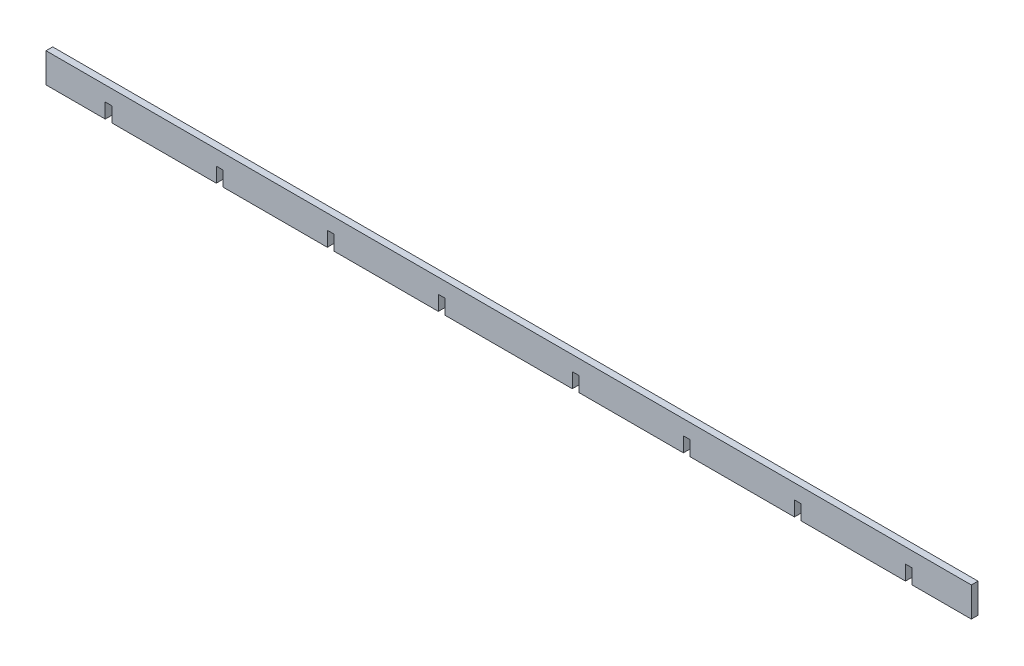
SolidWorks part; units mm, degrees
ref_plane "Front Plane" through (0, 0, 0) normal (0, 0, 1) x (1, 0, 0)
ref_plane "Top Plane" through (0, 0, 0) normal (0, 1, 0) x (1, 0, 0)
ref_plane "Right Plane" through (0, 0, 0) normal (1, 0, 0) x (0, 0, -1)
sketch "Sketch1" plane through (0, 0, 0) normal (0, 0, 1) x (1, 0, 0)
  line L0 (300, -40) -> (300, 40) construction
  line L1 (-178, 40) -> (2322, 40)
  line L2 (-178, 40) -> (-178, -40)
  line L3 (-178, -40) -> (2322, -40)
  line L4 (2322, 40) -> (2322, -40)
  line L5 (-18, -40) -> (0, -40)
  line L6 (-18, -40) -> (-18, 0)
  line L7 (-18, 0) -> (0, 0)
  line L8 (0, -40) -> (0, 0)
  line L9 (282, -40) -> (300, -40)
  line L10 (282, -40) -> (282, 0)
  line L11 (282, 0) -> (300, 0)
  line L12 (300, -40) -> (300, 0)
  line L13 (582, -40) -> (582, 40) construction
  line L14 (582, -40) -> (600, -40)
  line L15 (582, -40) -> (582, 0)
  line L16 (582, 0) -> (600, 0)
  line L17 (600, -40) -> (600, 0)
  line L18 (900, -40) -> (900, 40) construction
  line L19 (882, -40) -> (900, -40)
  line L20 (882, -40) -> (882, 0)
  line L21 (882, 0) -> (900, 0)
  line L22 (900, -40) -> (900, 0)
  line L24 (1244, -40) -> (1262, -40)
  line L25 (1244, -40) -> (1244, 0)
  line L26 (1244, 0) -> (1262, 0)
  line L27 (1262, -40) -> (1262, 0)
  line L28 (1544, -40) -> (1562, -40)
  line L29 (1544, -40) -> (1544, 0)
  line L30 (1544, 0) -> (1562, 0)
  line L31 (1562, -40) -> (1562, 0)
  line L32 (1844, -40) -> (1862, -40)
  line L33 (1844, -40) -> (1844, 0)
  line L34 (1844, 0) -> (1862, 0)
  line L35 (1862, -40) -> (1862, 0)
  line L36 (2144, -40) -> (2162, -40)
  line L37 (2144, -40) -> (2144, 0)
  line L38 (2144, 0) -> (2162, 0)
  line L39 (2162, -40) -> (2162, 0)
  dimension "D1" = 80
  dimension "D2" = 2500
extrude "Boss-Extrude1" add sketch "Sketch1" along normal blind 18 contours L39 L3 L4 L1 L2 L6 L7 L8 L10 L11 L12 L15 L16 L17 L20 L21 L22 L25 L26 L27 L29 L30 L31 L33 L34 L35 L37 L38
